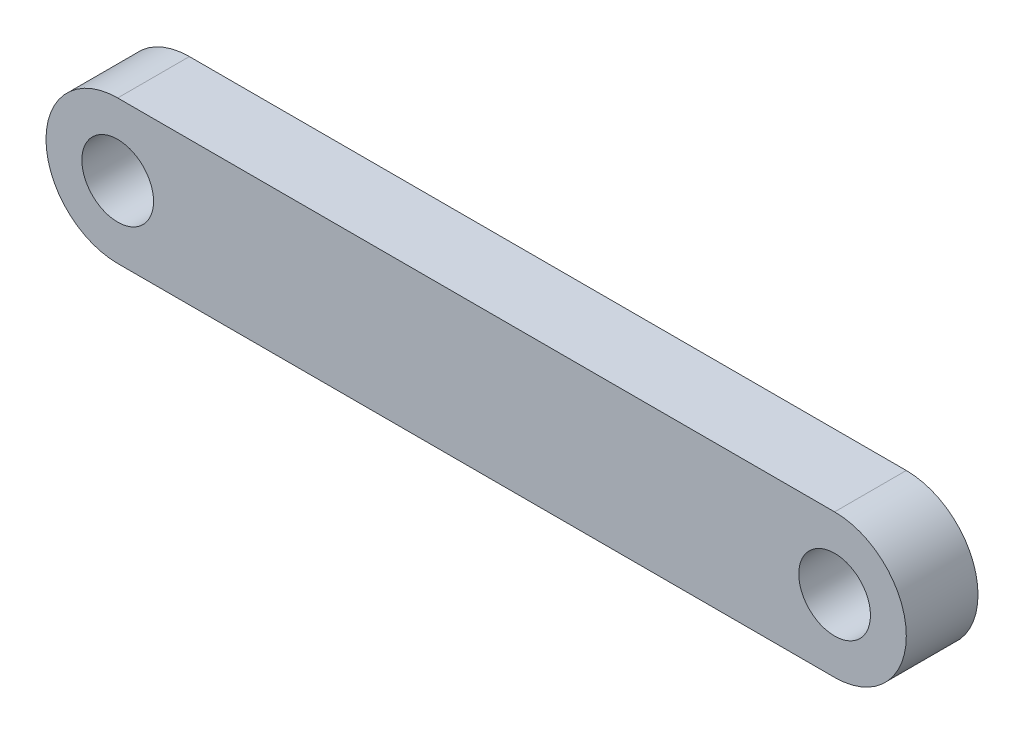
SolidWorks part; units mm, degrees
ref_plane "正面" through (0, 0, 0) normal (0, 0, 1) x (1, 0, 0)
ref_plane "平面" through (0, 0, 0) normal (0, 1, 0) x (1, 0, 0)
ref_plane "右側面" through (0, 0, 0) normal (1, 0, 0) x (0, 0, -1)
sketch "ｽｹｯﾁ2" plane through (0, 0, 0) normal (0, 0, 1) x (1, 0, 0)
  line L1 (-50, -10) -> (50, -10)
  line L2 (-50, -10) -> (-50, 10)
  line L3 (-50, 10) -> (50, 10)
  line L4 (50, -10) -> (50, 10)
  line L5 (-50, -10) -> (50, 10) construction
  line L6 (-50, 10) -> (50, -10) construction
  circle A0 centre (-50, 0) radius 10
  circle A1 centre (50, 0) radius 10
  circle A2 centre (-50, 0) radius 5
  circle A3 centre (50, 0) radius 5
  point P0 (0, 0)
extrude "ﾎﾞｽ - 押し出し1" add sketch "ｽｹｯﾁ2" along normal blind 10 contours A2 L2 A0 | A2 L2 A0 | A1 L3 A0 L1 | A3 L4 A1 | A3 L4 A1
